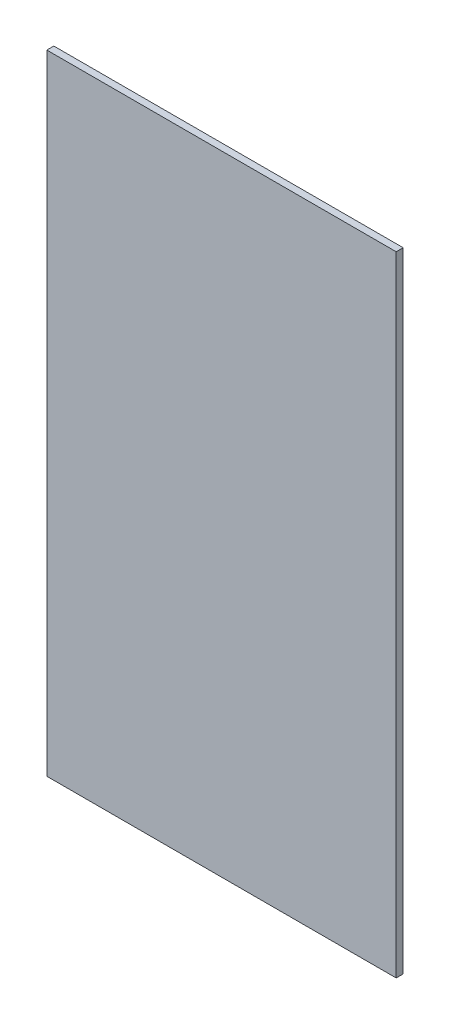
SolidWorks part; units mm, degrees
ref_plane "前视基准面" through (0, 0, 0) normal (0, 0, 1) x (1, 0, 0)
ref_plane "上视基准面" through (0, 0, 0) normal (0, 1, 0) x (1, 0, 0)
ref_plane "右视基准面" through (0, 0, 0) normal (1, 0, 0) x (0, 0, -1)
sketch "草图1" plane through (0, 0, 0) normal (0, 0, 1) x (1, 0, 0)
  line L1 (-2500, 4500) -> (2500, 4500)
  line L2 (-2500, 4500) -> (-2500, -4500)
  line L3 (-2500, -4500) -> (2500, -4500)
  line L4 (2500, 4500) -> (2500, -4500)
  line L5 (-2500, 4500) -> (2500, -4500) construction
  line L6 (-2500, -4500) -> (2500, 4500) construction
  point P0 (0, 0)
  dimension "D1" = 5000
  dimension "D2" = 9000
extrude "凸台-拉伸1" add sketch "草图1" along normal mid plane 100
equation "\"零件重量\"= \"SW-质量\""
